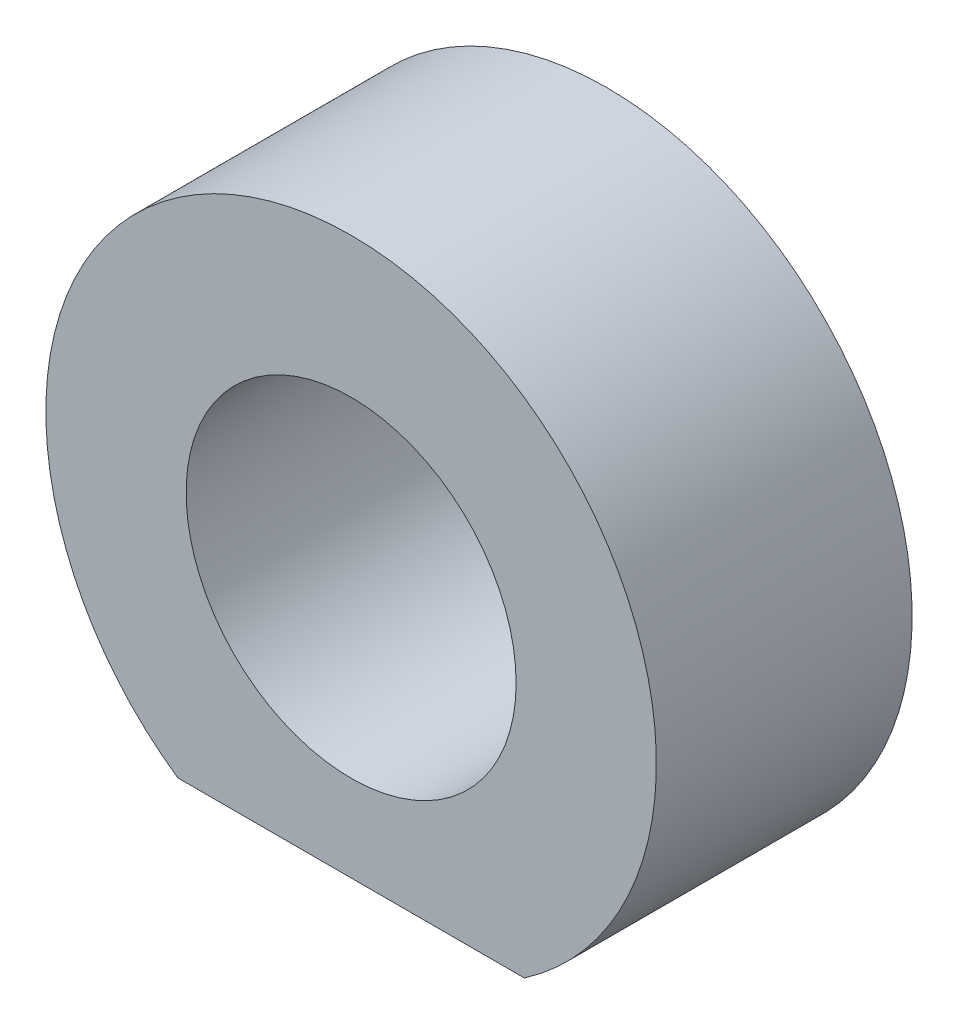
SolidWorks part; units mm, degrees
ref_plane "Ön Düzlem" through (0, 0, 0) normal (0, 0, 1) x (1, 0, 0)
ref_plane "Üst Düzlem" through (0, 0, 0) normal (0, 1, 0) x (1, 0, 0)
ref_plane "Sağ Düzlem" through (0, 0, 0) normal (1, 0, 0) x (0, 0, -1)
sketch "Çizim1" plane through (0, 0, 0) normal (0, 0, 1) x (1, 0, 0)
  line L1 (-10.5001, -15.2315) -> (10.5001, -15.2315)
  circle A0 centre (0, 0) radius 10
  arc A2 (10.5001, -15.2315) -> (-10.5001, -15.2315) centre (0, 0) ccw
  point P4 (0, 0)
  dimension "D1" = 37
  dimension "D2" = 20
  dimension "D3" = 15.2315
extrude "Yükseklik-Ekstrüzyon1" add sketch "Çizim1" along normal mid plane 15.5
